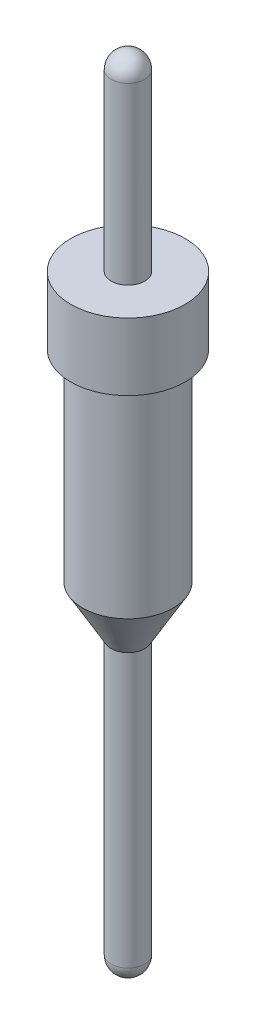
SolidWorks part; units mm, degrees
material "Beryllium Copper, UNS C17300"
ref_plane "Front Plane" through (0, 0, 0) normal (0, 0, 1) x (1, 0, 0)
ref_plane "Top Plane" through (0, 0, 0) normal (0, 1, 0) x (1, 0, 0)
ref_plane "Right Plane" through (0, 0, 0) normal (1, 0, 0) x (0, 0, -1)
sketch "Sketch1" plane through (0, 0, 0) normal (0, 0, 1) x (1, 0, 0)
  line L0 (0, 28.9926) -> (0, -77.4816) construction
  line L1 (0, -55) -> (0, 55) construction
  line L2 (-0.85, 0) -> (-0.85, -1)
  line L3 (55, 0) -> (-55, 0) construction
  line L4 (-0.85, -1) -> (-0.675, -1)
  line L5 (-0.675, -1) -> (-0.675, -4)
  line L6 (-0.675, -4) -> (-0.25, -4.7361)
  line L7 (-0.25, -4.7361) -> (-0.25, -8.8)
  line L8 (-0.85, 0) -> (-0.25, 0)
  line L9 (-0.25, 0) -> (-0.25, 2.6)
  line L10 (0, 2.85) -> (0, -9.05)
  arc A0 (-0.25, -8.8) -> (0, -9.05) centre (0, -8.8) ccw
  arc A1 (-0.25, 2.6) -> (0, 2.85) centre (0, 2.6) cw
  dimension "D1" = 30
  dimension "D2" = 1.7
  dimension "D3" = 1.35
  dimension "D4" = 1
  dimension "D5" = 4
  dimension "D6" = 0.5
  dimension "D7" = 2.85
  dimension "D8" = 1.7
  dimension "D9" = 8.8
  dimension "D10" = 9.05
revolve "Revolve1" add sketch "Sketch1" angle 360 about L0
